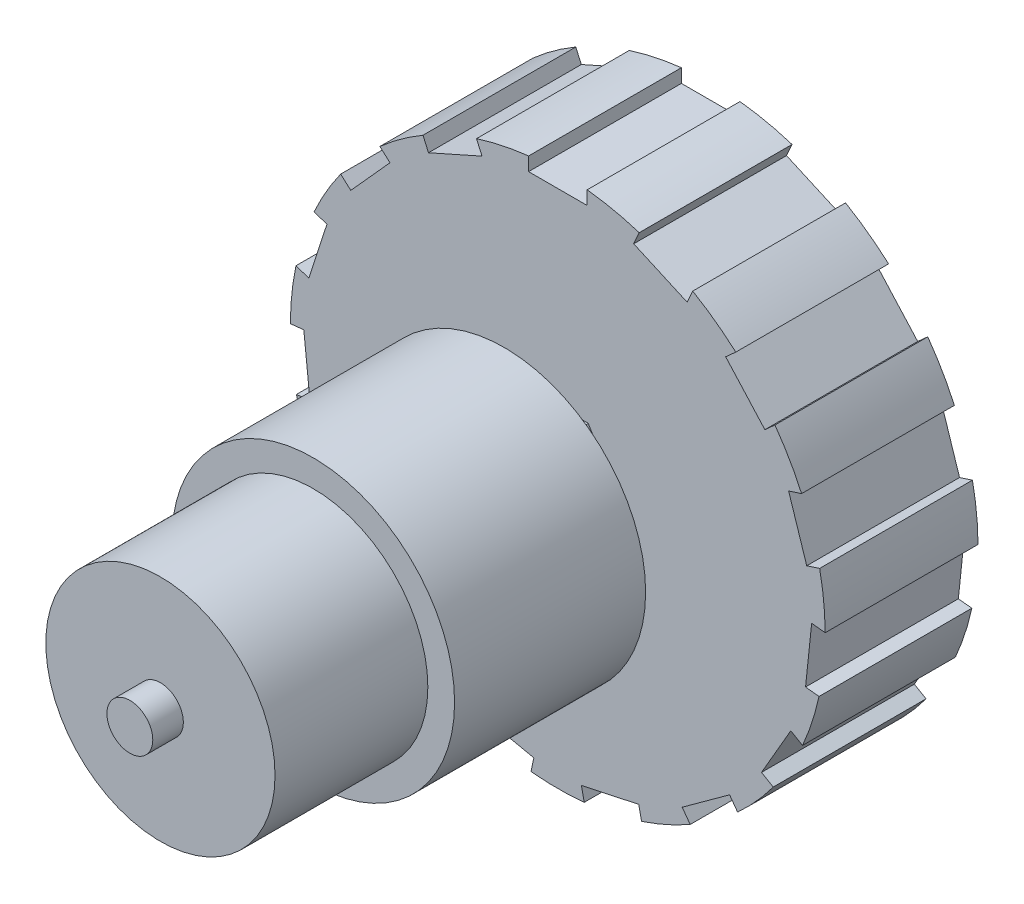
SolidWorks part; units mm, degrees
ref_plane "Front" through (0, 0, 0) normal (0, 0, 1) x (1, 0, 0)
ref_plane "Top" through (0, 0, 0) normal (0, 1, 0) x (1, 0, 0)
ref_plane "Right" through (0, 0, 0) normal (1, 0, 0) x (0, 0, -1)
sketch "Sketch1" plane through (0, 0, 0) normal (0, 0, 1) x (1, 0, 0)
  circle A0 centre (0, 0) radius 18.5
  dimension "D1" = 37
extrude "Boss-Extrude1" add sketch "Sketch1" along normal blind 25
sketch "Sketch2" plane through (0, 0, 25) normal (0, 0, 1) x (1, 0, 0)
  circle A0 centre (0, 0) radius 15
  circle A1 centre (0, 0) radius 18.5 construction
  dimension "D1" = 30
extrude "Boss-Extrude2" add sketch "Sketch2" along normal blind 20
ref_plane "Plane1" through (0, 0, -2) normal (0, 0, -1) x (-1, 0, 0)
sketch "Sketch10" plane through (0, 0, 0) normal (0, 0, -1) x (-1, 0, 0)
  circle A0 centre (0, 0) radius 7.5
  circle A1 centre (0, 0) radius 18.5 construction
  dimension "D1" = 15
extrude "Boss-Extrude8" add sketch "Sketch10" along normal blind 12
sketch "Sketch7" plane through (0, 0, -2) normal (0, 0, -1) x (-1, 0, 0)
  line L1 (12, 0) -> (6, 10.3923)
  line L2 (6, 10.3923) -> (-6, 10.3923)
  line L3 (-6, 10.3923) -> (-12, 0)
  line L4 (-12, 0) -> (-6, -10.3923)
  line L5 (-6, -10.3923) -> (6, -10.3923)
  line L6 (6, -10.3923) -> (12, 0)
  circle A1 centre (0, 0) radius 10.3923 construction
  circle A3 centre (0, 0) radius 7.5
  circle A4 centre (0, 0) radius 7.5
  dimension "D1" = 12
  dimension "D2" = 0
extrude "Boss-Extrude6" add sketch "Sketch7" along normal blind 3 separate body
sketch "Sketch4" plane through (0, 0, -5) normal (0, 0, -1) x (-1, 0, 0)
  circle A0 centre (0, 0) radius 3
  circle A1 centre (0, 0) radius 3 construction
  dimension "D1" = 6
extrude "Boss-Extrude4" add sketch "Sketch4" along normal blind 22 separate body
sketch "Sketch5" plane through (-0.0105, 7.6176, 0) normal (-0.0014, 1, 0) x (1, 0.0014, 0)
  line L0 (3, 27) -> (-3, 27) construction
  circle A0 centre (-0.0625, 19) radius 1.9083
  dimension "D1" = 8
extrude "Cut-Extrude1" cut sketch "Sketch5" against normal blind 22
sketch "Sketch6" plane through (0, 0, 45) normal (0, 0, 1) x (1, 0, 0)
  circle A0 centre (0, 0) radius 3
  dimension "D1" = 6
extrude "Boss-Extrude5" add sketch "Sketch6" along normal blind 4
ref_plane "Plane2" through (0, 0, -7) normal (0, 0, -1) x (-1, 0, 0)
sketch "Sketch8" plane through (0, 0, -7) normal (0, 0, -1) x (-1, 0, 0)
  circle A0 centre (0, 0) radius 35
  dimension "D1" = 70
extrude "Boss-Extrude7" add sketch "Sketch8" along normal blind 20
sketch "Sketch9" plane through (0, 0, -27) normal (0, 0, -1) x (-1, 0, 0)
  line L78 (-3.8483, 35.2018) -> (3.8176, 35.2018)
  line L79 (-3.8483, 35.2018) -> (-3.8483, 33.0116)
  line L80 (-3.8483, 33.0116) -> (3.8176, 33.0116)
  line L81 (3.8176, 35.2018) -> (3.8176, 33.0116)
extrude "Cut-Extrude2" cut sketch "Sketch9" against normal blind 20
pattern_circular "CirPattern1" count 15 over 360 about axis through (0, 0, 0) along (0, 0, 1) of "Cut-Extrude2"
